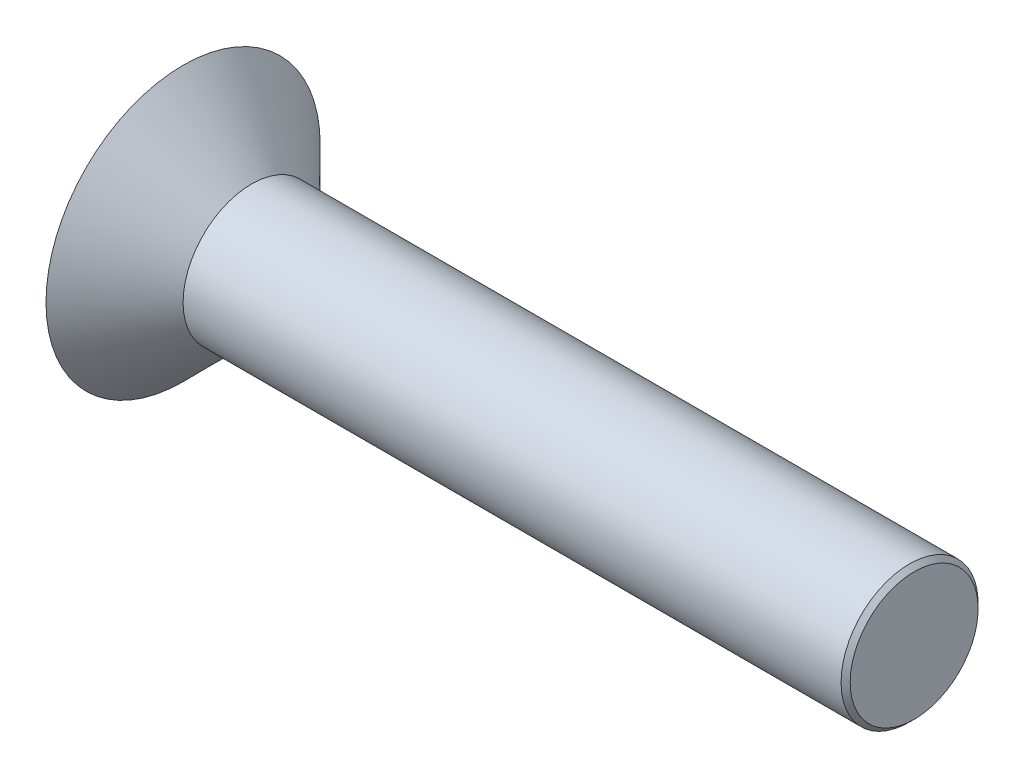
SolidWorks part; units mm, degrees
ref_plane "前视基准面" through (0, 0, 0) normal (0, 0, 1) x (1, 0, 0)
ref_plane "上视基准面" through (0, 0, 0) normal (0, 1, 0) x (1, 0, 0)
ref_plane "右视基准面" through (0, 0, 0) normal (1, 0, 0) x (0, 0, -1)
sketch "草图1" plane through (0, 0, 0) normal (0, 1, 0) x (1, 0, 0)
  line L0 (0, 0) -> (16, 0) construction
  line L1 (0, 0) -> (0, 3)
  line L2 (0, 3) -> (1.5, 1.5)
  line L3 (1.5, 1.5) -> (16, 1.5)
  line L4 (16, 1.5) -> (16, 0)
  line L5 (0, 0) -> (16, 0)
  dimension "D1" = 45
  dimension "D2" = 3
  dimension "D3" = 6
  dimension "D4" = 16
revolve "主体部分" add sketch "草图1" angle 360 about L0
cosmetic thread "装饰螺纹线1" parameters "D2"=2.459
sketch "草图2" plane through (0, 0, 0) normal (-1, 0, 0) x (0, 0, 1)
  line L1 (1.4434, 0) -> (0.7217, 1.25)
  line L2 (0.7217, 1.25) -> (-0.7217, 1.25)
  line L3 (-0.7217, 1.25) -> (-1.4434, 0)
  line L4 (-1.4434, 0) -> (-0.7217, -1.25)
  line L5 (-0.7217, -1.25) -> (0.7217, -1.25)
  line L6 (0.7217, -1.25) -> (1.4434, 0)
  circle A0 centre (0, 0) radius 1.25 construction
  dimension "D1" = 2.5
extrude "沉头内六角" cut sketch "草图2" against normal blind 1.2
chamfer "修饰性倒角" distance 0.1 angle 45 1 edges at (16, 0, 1.5)
